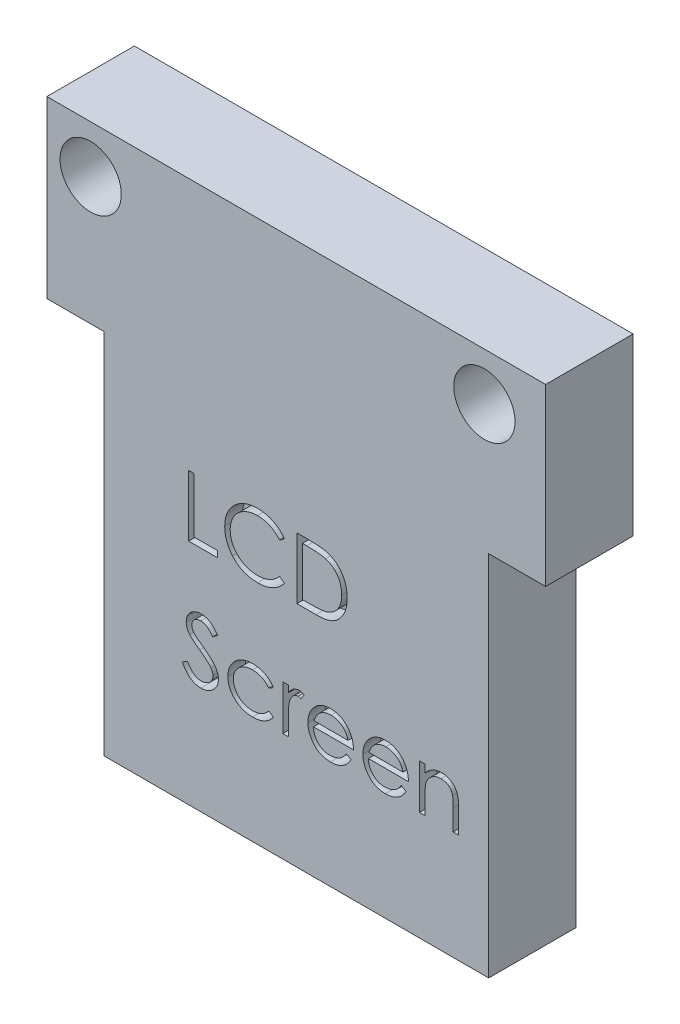
SolidWorks part; units mm, degrees
ref_plane "Front Plane" through (0, 0, 0) normal (0, 0, 1) x (1, 0, 0)
ref_plane "Top Plane" through (0, 0, 0) normal (0, 1, 0) x (1, 0, 0)
ref_plane "Right Plane" through (0, 0, 0) normal (1, 0, 0) x (0, 0, -1)
sketch "Sketch1" plane through (0, 0, 0) normal (0, 0, 1) x (1, 0, 0)
  line L1 (-14.25, 15.5) -> (14.25, 15.5)
  line L2 (-14.25, 15.5) -> (-14.25, -15.5)
  line L3 (-14.25, -15.5) -> (14.25, -15.5)
  line L4 (14.25, 15.5) -> (14.25, -15.5)
  line L5 (-14.25, 15.5) -> (14.25, -15.5) construction
  line L6 (-14.25, -15.5) -> (14.25, 15.5) construction
  line L7 (-14.25, 5.5) -> (-11, 5.5)
  line L8 (-14.25, 5.5) -> (-14.25, -15.5)
  line L9 (-14.25, -15.5) -> (-11, -15.5)
  line L10 (-11, 5.5) -> (-11, -15.5)
  line L11 (14.25, 5.5) -> (11, 5.5)
  line L12 (14.25, 5.5) -> (14.25, -15.5)
  line L13 (14.25, -15.5) -> (11, -15.5)
  line L14 (11, 5.5) -> (11, -15.5)
  circle A0 centre (-11.75, 12.7807) radius 1.75
  circle A1 centre (10.75, 12.7807) radius 1.75
  point P0 (0, 0)
  dimension "D3" = 3.5
  dimension "D4" = 3.5
  dimension "D1" = 28.5
  dimension "D2" = 31
  dimension "D5" = 22.5
  dimension "D6" = 2.5
  dimension "D7" = 3.25
  dimension "D8" = 3.25
  dimension "D9" = 21
  dimension "D10" = 21
extrude "Boss-Extrude1" add sketch "Sketch1" along normal blind 5 contours L14 L11 L4 L1 L2 L7 L10 L3 A1 A0
sketch "Sketch2" plane through (0, 0, 5) normal (0, 0, 1) x (1, 0, 0)
  line L0 (-6.6015, -2.4537) -> (11, -2.4537) construction
  line L3 (11, 5.5) -> (11, -15.5) construction
  text T0 "LCD\r\nScreen"
extrude "Cut-Extrude1" cut sketch "Sketch2" against normal blind 1
